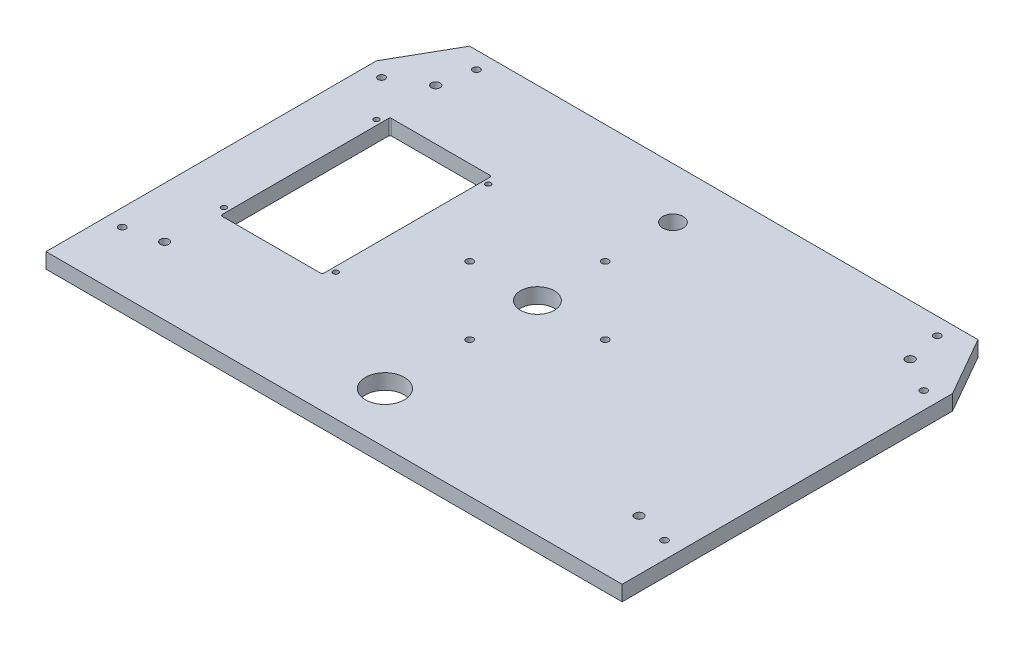
SolidWorks part; units mm, degrees
ref_plane "Plan de face" through (0, 0, 0) normal (0, 0, 1) x (1, 0, 0)
ref_plane "Plan de dessus" through (0, 0, 0) normal (0, 1, 0) x (1, 0, 0)
ref_plane "Plan de droite" through (0, 0, 0) normal (1, 0, 0) x (0, 0, -1)
sketch "Esquisse3" plane through (0, 0, 0) normal (0, 1, 0) x (1, 0, 0)
  line L0 (-281.7629, 0) -> (308.2067, 0) construction
  line L1 (0, 166.4902) -> (0, -269.1166) construction
  line L4 (-160, -46) -> (-160, 46) construction
  line L5 (-156, 50) -> (-149, 50) construction
  line L6 (-145, 46) -> (-145, -46) construction
  line L7 (-105, 0) -> (-105, 31) construction
  line L8 (-101, 35) -> (-74, 35) construction
  line L9 (-70, 31) -> (-70, -31) construction
  line L11 (-105, 0) -> (-105, -31) construction
  line L12 (-101, -35) -> (-74, -35) construction
  line L13 (-156, -50) -> (-149, -50) construction
  line L17 (156, 50) -> (149, 50) construction
  line L18 (156, -50) -> (149, -50) construction
  line L19 (145, 46) -> (145, -46) construction
  line L20 (160, -46) -> (160, 46) construction
  line L21 (105, 0) -> (105, 31) construction
  line L22 (101, -35) -> (74, -35) construction
  line L23 (105, 0) -> (105, -31) construction
  line L24 (70, 31) -> (70, -31) construction
  line L25 (101, 35) -> (74, 35) construction
  line L26 (150, 110) -> (-150, 110)
  line L34 (-170, 75) -> (-150, 110)
  line L35 (170, 75) -> (150, 110)
  line L38 (-170, 75) -> (-170, 0)
  line L39 (-170, 0) -> (-170, -120)
  line L40 (170, -120) -> (170, 0)
  line L41 (170, 0) -> (170, 75)
  line L43 (-170, -120) -> (-150, -140)
  line L44 (150, -140) -> (170, -120)
  line L45 (-150, -140) -> (-120, -140)
  line L46 (-120, -140) -> (-120, -55) construction
  line L47 (-120, -55) -> (120, -55) construction
  line L48 (120, -55) -> (120, -140) construction
  line L49 (120, -140) -> (150, -140)
  line L50 (-170, 75) -> (170, 75) construction
  line L51 (-170, 0) -> (-220, 0) construction
  line L52 (-220, 0) -> (-170, 75) construction
  line L53 (-220, 0) -> (-170, -120) construction
  line L54 (-130, -140) -> (-130, -220) construction
  line L55 (-130, -220) -> (130, -220) construction
  line L56 (130, -140) -> (130, -220) construction
  line L57 (-170, -120) -> (-130, -220) construction
  line L58 (-120, -140) -> (120, -140)
  line L59 (-170, -120) -> (170, -120)
  arc A0 (-149, 50) -> (-145, 46) centre (-149, 46) cw construction
  arc A1 (-74, 35) -> (-70, 31) centre (-74, 31) cw construction
  arc A2 (-105, 31) -> (-101, 35) centre (-101, 31) cw construction
  arc A3 (-160, 46) -> (-156, 50) centre (-156, 46) cw construction
  arc A4 (-105, -31) -> (-101, -35) centre (-101, -31) ccw construction
  arc A5 (-74, -35) -> (-70, -31) centre (-74, -31) ccw construction
  arc A6 (-160, -46) -> (-156, -50) centre (-156, -46) ccw construction
  arc A7 (-149, -50) -> (-145, -46) centre (-149, -46) ccw construction
  arc A8 (149, 50) -> (145, 46) centre (149, 46) ccw construction
  arc A9 (160, 46) -> (156, 50) centre (156, 46) ccw construction
  arc A10 (149, -50) -> (145, -46) centre (149, -46) cw construction
  arc A11 (160, -46) -> (156, -50) centre (156, -46) cw construction
  arc A12 (74, -35) -> (70, -31) centre (74, -31) cw construction
  arc A13 (105, -31) -> (101, -35) centre (101, -31) cw construction
  arc A14 (105, 31) -> (101, 35) centre (101, 31) ccw construction
  arc A15 (74, 35) -> (70, 31) centre (74, 31) ccw construction
  circle A16 centre (-140, 80) radius 2.55
  circle A17 centre (-140, -80) radius 2.55
  circle A18 centre (140, -80) radius 2.55
  circle A19 centre (140, 80) radius 2.55
  point P6 (-170, 110)
  point P16 (-105, 15.5)
  point P19 (-145, 50)
  point P22 (-70, 35)
  point P25 (-105, 35)
  point P28 (-160, 50)
  point P32 (-70, 0)
  point P37 (-105, -35)
  point P38 (-70, -35)
  point P40 (-145, 0)
  point P41 (-160, 0)
  point P45 (-160, -50)
  point P46 (-145, -50)
  point P47 (0, 110)
  point P48 (-170, 0)
  point P51 (0, -110)
  point P64 (145, -50)
  point P65 (160, -50)
  point P75 (70, -35)
  point P76 (105, -35)
  point P81 (105, 35)
  point P82 (70, 35)
  point P83 (0, -269.1166)
  point P85 (0, 110)
  point P94 (-170, 0)
  point P97 (170, 0)
  point P100 (0, -130)
  dimension "D7" = 4
  dimension "D10" = 5.1
  dimension "D2" = 300
  dimension "D3" = 35
  dimension "D4" = 15
  dimension "D5" = 70
  dimension "D6" = 40
  dimension "D14" = 30
  dimension "D13" = 110
  dimension "D8" = 35
  dimension "D9" = 50
  dimension "D11" = 240
  dimension "D12" = 340
  dimension "D15" = 120
  dimension "D16" = 75
  dimension "D17" = 140
  dimension "D18" = 80
  dimension "D19" = 85
  dimension "D20" = 140
  dimension "D21" = 150
  dimension "D22" = 28.2843
  dimension "D23" = 40.3113
  dimension "D24" = 120
  dimension "D25" = 50
  dimension "D26" = 130
  dimension "D27" = 90.1388
  dimension "D28" = 80
  dimension "D29" = 10
  dimension "D30" = 107.7033
  dimension "D31" = 130
  dimension "D32" = 40
  dimension "D33" = 230
extrude "structure" add sketch "Esquisse3" against normal blind 9 contours L39 L59 L40 L41 L35 L26 L34 L38 A17 A16 A18 A19
sketch "Esquisse4" plane through (0, 0, 0) normal (0, 1, 0) x (1, 0, 0)
  line L0 (0, 110) -> (0, -120) construction
  line L3 (-170, 0) -> (170, 0) construction
  line L6 (150, 110) -> (-150, 110) construction
  line L7 (-170, -120) -> (170, -120) construction
  line L8 (170, -120) -> (170, 75) construction
  line L9 (-170, 75) -> (-170, -120) construction
  circle A0 centre (0, 0) radius 10
  circle A1 centre (0, -90) radius 11.5
  circle A2 centre (0, 0) radius 40 construction
  circle A3 centre (0, 40) radius 2.05
  circle A4 centre (40, 0) radius 2.05
  circle A5 centre (0, -40) radius 2.05
  circle A6 centre (-40, 0) radius 2.05
  circle A7 centre (0, 0) radius 30.8 construction
  circle A8 centre (0, 80) radius 6
  point P29 (0, 0)
  dimension "D1" = 23
  dimension "D3" = 20
  dimension "D4" = 4.1
  dimension "D6" = 80
  dimension "D7" = 61.6
  dimension "D8" = 12
  dimension "D2" = 90
  dimension "D9" = 80
  dimension "D5" = 4
extrude "Enlèv. mat.-Extru.1" cut sketch "Esquisse4" against normal blind 10
sketch "Esquisse5" plane through (0, 0, 0) normal (0, 1, 0) x (1, 0, 0)
  line L0 (0, 119.5004) -> (0, -133.6316) construction
  line L6 (-170, 75) -> (-170, -120)
  line L7 (-170, -120) -> (170, -120)
  line L8 (170, -120) -> (170, 75)
  line L9 (170, 75) -> (150, 110)
  line L10 (150, 110) -> (-150, 110)
  line L11 (-150, 110) -> (-170, 75)
  line L12 (-170, 75) -> (-170, -120)
  line L13 (-170, -120) -> (170, -120)
  line L14 (170, -120) -> (170, 75)
  line L15 (170, 75) -> (150, 110)
  line L16 (150, 110) -> (-150, 110)
  line L17 (-150, 110) -> (-170, 75)
  circle A0 centre (-140, 80) radius 2.55 construction
  circle A1 centre (-140, 80) radius 2.55
  circle A2 centre (-140, -80) radius 2.55 construction
  circle A3 centre (-140, -80) radius 2.55
  circle A4 centre (-136, 100) radius 2.05
  circle A5 centre (-160, 68) radius 2.05
  circle A6 centre (-160, -85) radius 2.05
  circle A7 centre (160, -85) radius 2.05
  circle A8 centre (160, 68) radius 2.05
  circle A9 centre (136, 100) radius 2.05
  dimension "D2" = 4.1
  dimension "D3" = 20
  dimension "D4" = 20
  dimension "D5" = 4
  dimension "D6" = 12
  dimension "D7" = 5
  dimension "D8" = 20
  dimension "D1" = 0
extrude "Enlèv. mat.-Extru.2" cut sketch "Esquisse5" against normal blind 10 flip side to cut
sketch "Esquisse6" plane through (0, 0, 0) normal (0, 1, 0) x (1, 0, 0)
  line L0 (-170, 0) -> (170, 0) construction
  line L1 (-140, 45) -> (-74, 45) construction
  line L2 (-140, 45) -> (-140, -45) construction
  line L3 (-140, -45) -> (-74, -45) construction
  line L4 (-74, 45) -> (-74, -45) construction
  line L5 (-140, 45) -> (-74, -45) construction
  line L6 (-170, 75) -> (-170, -120)
  line L7 (-170, -120) -> (170, -120)
  line L8 (170, -120) -> (170, 75)
  line L9 (170, 75) -> (150, 110)
  line L10 (150, 110) -> (-150, 110)
  line L11 (-150, 110) -> (-170, 75)
  line L12 (-170, 75) -> (-170, -120)
  line L13 (-170, -120) -> (170, -120)
  line L14 (170, -120) -> (170, 75)
  line L15 (170, 75) -> (150, 110)
  line L16 (150, 110) -> (-150, 110)
  line L17 (-150, 110) -> (-170, 75)
  line L18 (-140, -45) -> (-74, 45) construction
  line L20 (-78, -50) -> (-136, -50)
  line L21 (-77, -49) -> (-77, 49)
  line L22 (-78, 50) -> (-136, 50)
  line L23 (-137, -49) -> (-137, 49)
  line L24 (-77, -50) -> (-137, 50) construction
  line L25 (-77, 50) -> (-137, -50) construction
  circle A0 centre (-140, 45) radius 1.55
  circle A1 centre (-74, 45) radius 1.55
  circle A2 centre (-140, -45) radius 1.55
  circle A3 centre (-74, -45) radius 1.55
  arc A4 (-78, -50) -> (-77, -49) centre (-78, -49) ccw
  arc A5 (-136, -50) -> (-137, -49) centre (-136, -49) cw
  arc A6 (-77, 49) -> (-78, 50) centre (-78, 49) ccw
  arc A7 (-136, 50) -> (-137, 49) centre (-136, 49) ccw
  point P2 (-107, 0)
  point P18 (-107, 0)
  dimension "D5" = 3.1
  dimension "D8" = 1
  dimension "D2" = 90
  dimension "D3" = 66
  dimension "D4" = 30
  dimension "D6" = 100
  dimension "D7" = 60
  dimension "D1" = 0
extrude "Enlèv. mat.-Extru.3" cut sketch "Esquisse6" against normal through all contours L23 L20 L21 L22 | A2 | A0 | A1 | A3
